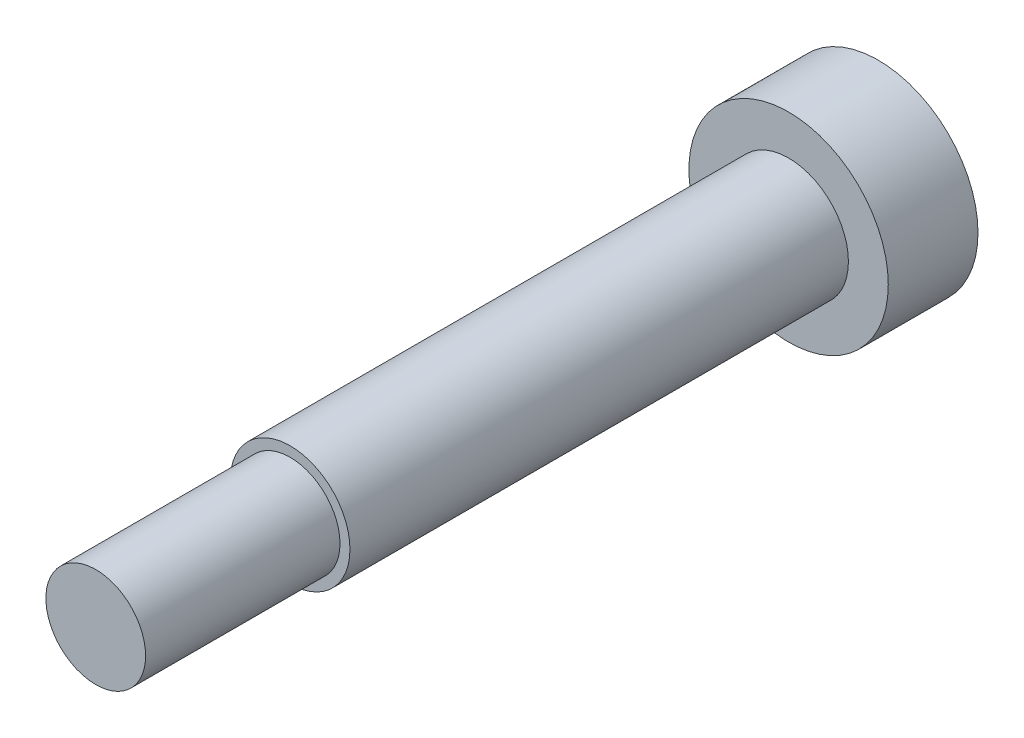
SolidWorks part; units mm, degrees
material "6061 合金"
ref_plane "前视基准面" through (0, 0, 0) normal (0, 0, 1) x (1, 0, 0)
ref_plane "上视基准面" through (0, 0, 0) normal (0, 1, 0) x (1, 0, 0)
ref_plane "右视基准面" through (0, 0, 0) normal (1, 0, 0) x (0, 0, -1)
sketch "草图1" plane through (0, 0, 0) normal (0, 0, 1) x (1, 0, 0)
  circle A0 centre (0, 0) radius 5
  dimension "D1" = 10
extrude "凸台-拉伸1" add sketch "草图1" along normal blind 4.5
sketch "草图2" plane through (0, 0, 4.5) normal (0, 0, 1) x (1, 0, 0)
  circle A0 centre (0, 0) radius 3
  dimension "D1" = 6
extrude "凸台-拉伸2" add sketch "草图2" along normal blind 25
sketch "草图3" plane through (0, 0, 29.5) normal (0, 0, 1) x (1, 0, 0)
  circle A0 centre (0, 0) radius 2.5
  dimension "D1" = 5
extrude "凸台-拉伸3" add sketch "草图3" along normal blind 9.75
cosmetic thread "装饰螺纹线1" parameters "D2"=4
